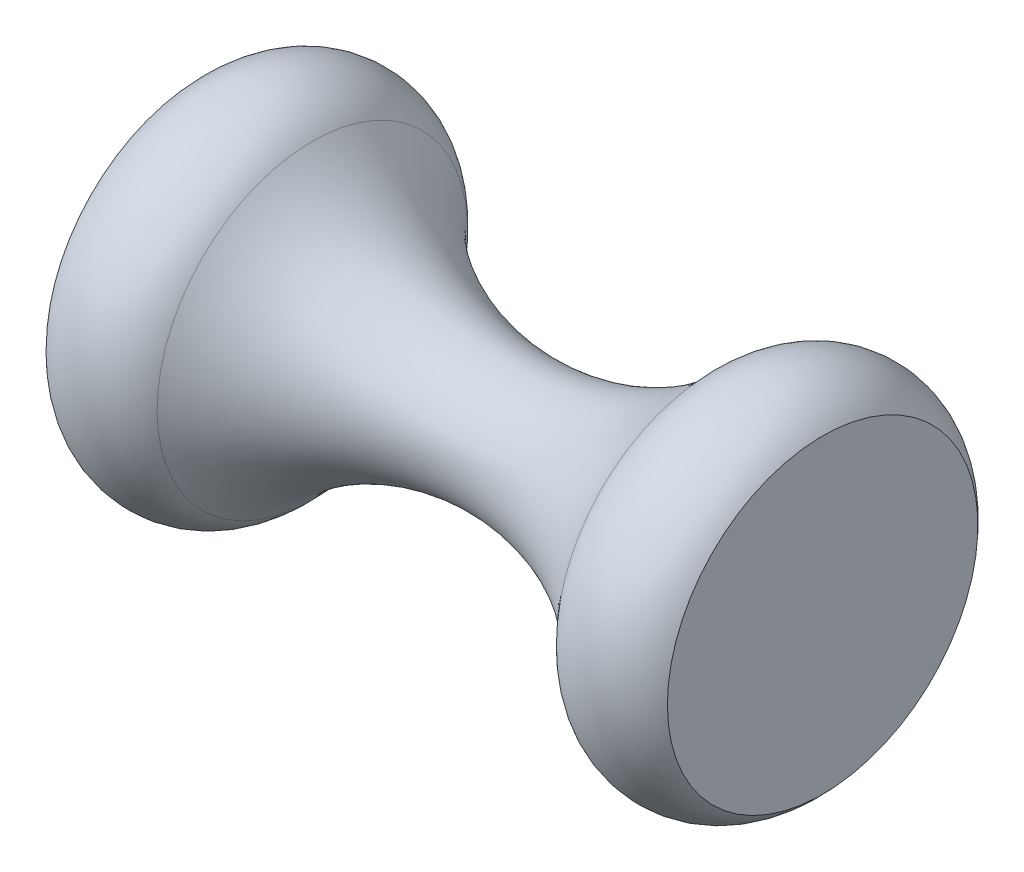
SolidWorks part; units mm, degrees
ref_plane "Front Plane" through (0, 0, 0) normal (0, 0, 1) x (1, 0, 0)
ref_plane "Top Plane" through (0, 0, 0) normal (0, 1, 0) x (1, 0, 0)
ref_plane "Right Plane" through (0, 0, 0) normal (1, 0, 0) x (0, 0, -1)
sketch "Sketch1" plane through (0, 0, 0) normal (0, 0, 1) x (1, 0, 0)
  line L0 (-25, 0) -> (25, 0)
  line L1 (-25, 0) -> (-25, -12.5)
  line L2 (25, 0) -> (25, -12.5)
  line L3 (25, -12.5) -> (-25, -12.5) construction
  line L4 (0, 0) -> (0, -26) construction
  arc A0 (16.0857, -12.5) -> (-16.0857, -12.5) centre (0, -26) ccw
  arc A1 (-25, -12.5) -> (-16.0857, -12.5) centre (-20.5429, -8.7593) ccw
  arc A2 (16.0857, -12.5) -> (25, -12.5) centre (20.5429, -8.7593) ccw
  dimension "D3" = 42
  dimension "D1" = 50
  dimension "D2" = 12.5
  dimension "D4" = 26
revolve "Revolve1" add sketch "Sketch1" angle 360 about L0
